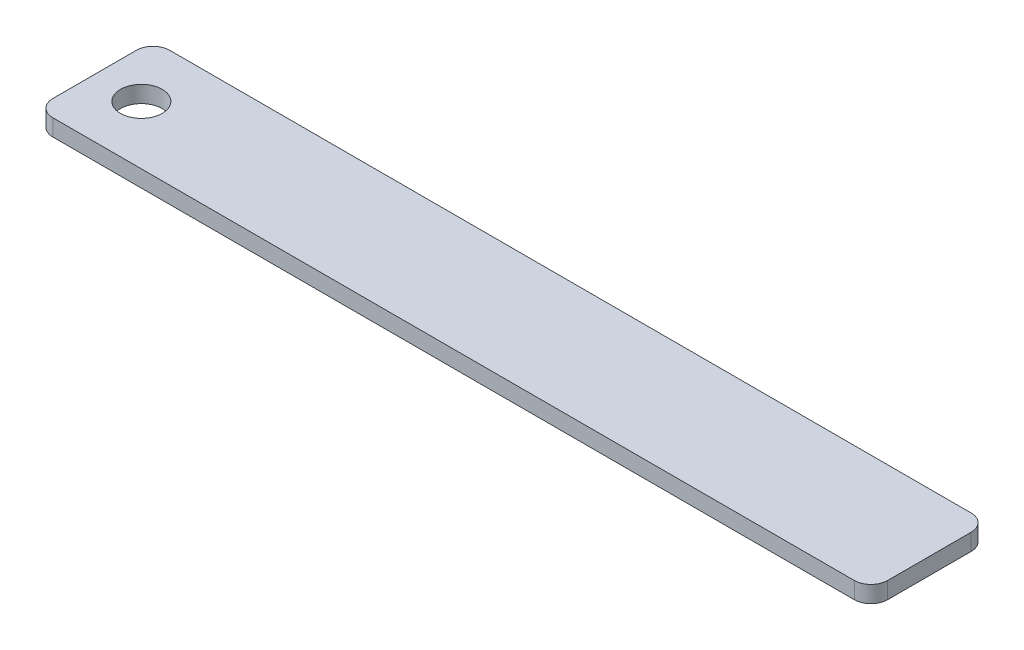
SolidWorks part; units mm, degrees
ref_plane "Front Plane" through (0, 0, 0) normal (0, 0, 1) x (1, 0, 0)
ref_plane "Top Plane" through (0, 0, 0) normal (0, 1, 0) x (1, 0, 0)
ref_plane "Right Plane" through (0, 0, 0) normal (1, 0, 0) x (0, 0, -1)
sketch "Sketch1" plane through (0, 0, 0) normal (0, 1, 0) x (1, 0, 0)
  line L1 (-31.75, -4.445) -> (31.75, -4.445)
  line L2 (-31.75, -4.445) -> (-31.75, 4.445)
  line L3 (-31.75, 4.445) -> (31.75, 4.445)
  line L4 (31.75, -4.445) -> (31.75, 4.445)
  line L5 (-31.75, -4.445) -> (31.75, 4.445) construction
  line L6 (-31.75, 4.445) -> (31.75, -4.445) construction
  circle A0 centre (-28.194, 0) radius 1.5875
  point P0 (0, 0)
  point P8 (0, 0)
  dimension "D3" = 3.175
  dimension "D4" = 3.556
  dimension "D1" = 8.89
  dimension "D2" = 63.5
extrude "Boss-Extrude1" add sketch "Sketch1" along normal blind 1.27
fillet "Fillet1" radius 1.27 4 edges at (-31.75, 0.635, -4.445) (-31.75, 0.635, 4.445) (31.75, 0.635, -4.445) (31.75, 0.635, 4.445)
